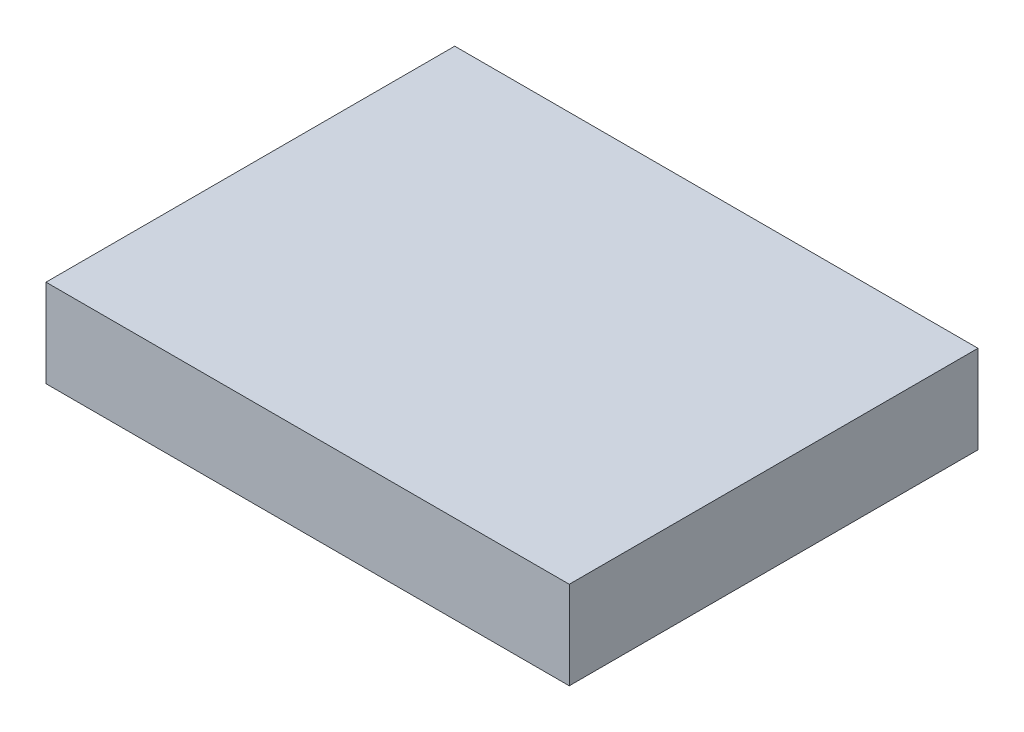
SolidWorks part; units mm, degrees
ref_plane "前基準面" through (0, 0, 0) normal (0, 0, 1) x (1, 0, 0)
ref_plane "上基準面" through (0, 0, 0) normal (0, 1, 0) x (1, 0, 0)
ref_plane "右基準面" through (0, 0, 0) normal (1, 0, 0) x (0, 0, -1)
sketch "草圖1" plane through (0, 0, 0) normal (0, 1, 0) x (1, 0, 0)
  line L1 (-34.5, 26.95) -> (34.5, 26.95)
  line L2 (-34.5, 26.95) -> (-34.5, -26.95)
  line L3 (-34.5, -26.95) -> (34.5, -26.95)
  line L4 (34.5, 26.95) -> (34.5, -26.95)
  line L5 (-34.5, 26.95) -> (34.5, -26.95) construction
  line L6 (-34.5, -26.95) -> (34.5, 26.95) construction
  point P0 (0, 0)
  dimension "D1" = 69
  dimension "D2" = 53.9
extrude "填料-伸長1" add sketch "草圖1" along normal blind 11.6
sketch "草圖2" plane through (0, 11.6, 0) normal (0, 1, 0) x (1, 0, 0)
  text T0 "Arduino"
